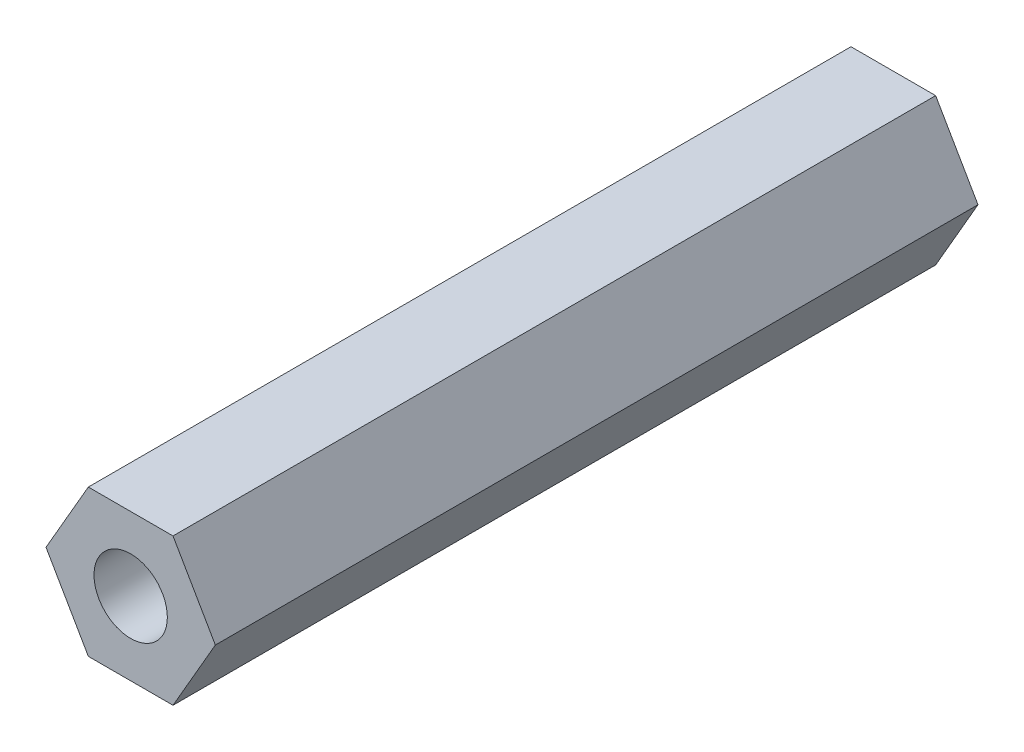
SolidWorks part; units mm, degrees
ref_plane "前视基准面" through (0, 0, 0) normal (0, 0, 1) x (1, 0, 0)
ref_plane "上视基准面" through (0, 0, 0) normal (0, 1, 0) x (1, 0, 0)
ref_plane "右视基准面" through (0, 0, 0) normal (1, 0, 0) x (0, 0, -1)
sketch "草图1" plane through (0, 0, 0) normal (0, 0, 1) x (1, 0, 0)
  line L1 (2.8868, 0) -> (1.4434, 2.5)
  line L2 (1.4434, 2.5) -> (-1.4434, 2.5)
  line L3 (-1.4434, 2.5) -> (-2.8868, 0)
  line L4 (-2.8868, 0) -> (-1.4434, -2.5)
  line L5 (-1.4434, -2.5) -> (1.4434, -2.5)
  line L6 (1.4434, -2.5) -> (2.8868, 0)
  circle A0 centre (0, 0) radius 2.5 construction
  circle A1 centre (0, 0) radius 1.5
  dimension "D2" = 3
  dimension "D1" = 5
extrude "凸台-拉伸1" add sketch "草图1" along normal blind 26 contours A1 | L5 L6 L1 L2 L3 L4 A1
hole_wizard "M3 螺纹孔1" positions "草图2" profile "草图3" tap size "M3" standard "GB"
sketch "草图2" plane through (0, 0, 26) normal (0, 0, 1) x (1, 0, 0)
  point P0 (0, 0)
sketch "草图3" plane through (0, 0, 26) normal (1, 0, 0) x (0, -1, 0)
  line L0 (0, 0) -> (0, 8.2511)
  line L1 (0, 8.2511) -> (1.25, 7.5)
  line L2 (1.25, 7.5) -> (1.25, 0)
  line L5 (1.25, 0) -> (0, 0)
  line L10 (0, 8.2511) -> (-1.25, 7.5) construction
  line L11 (0, -6.35) -> (0, 107.95) construction
  dimension "螺纹孔钻头直径" = 2.5
  dimension "螺纹孔钻头深度" = 7.5
  dimension "导头角度" = 118
cosmetic thread "孔螺蚊线1"
